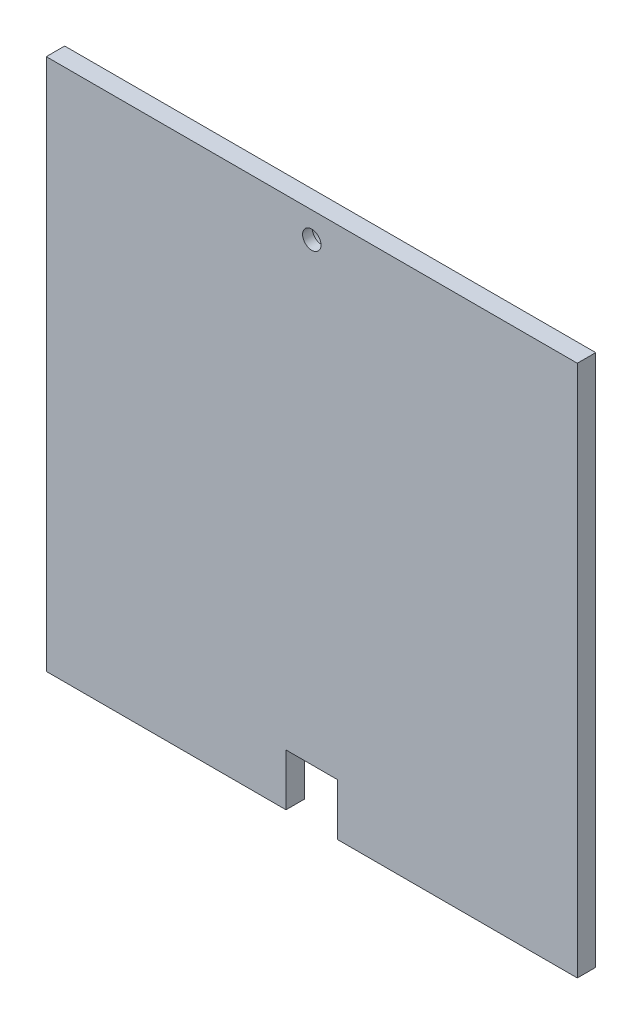
SolidWorks part; units mm, degrees
ref_plane "Plan de face" through (0, 0, 0) normal (0, 0, 1) x (1, 0, 0)
ref_plane "Plan de dessus" through (0, 0, 0) normal (0, 1, 0) x (1, 0, 0)
ref_plane "Plan de droite" through (0, 0, 0) normal (1, 0, 0) x (0, 0, -1)
sketch "Esquisse1" plane through (0, 0, 0) normal (0, 0, 1) x (1, 0, 0)
  line L0 (-83.3981, -1000) -> (-125.3981, -1000) construction
  line L1 (164.0336, 0) -> (-268.4317, 0)
  line L2 (164.0336, 0) -> (164.0336, -1000)
  line L3 (164.0336, -1000) -> (-268.4317, -1000)
  line L4 (-268.4317, 0) -> (-268.4317, -1000)
  line L5 (164.0336, 0) -> (-268.4317, -1000) construction
  line L6 (164.0336, -1000) -> (-268.4317, 0) construction
  line L7 (-83.3981, 0) -> (-125.3981, 0) construction
  point P0 (-52.199, -500)
extrude "Boss.-Extru.1" add sketch "Esquisse1" along normal blind 15
sketch "Esquisse2" plane through (164.0336, 0, 0) normal (1, 0, 0) x (0, 0, -1)
  line L0 (0, -1000) -> (0, 0) construction
  line L1 (-15, -1000) -> (0, -1000)
  line L2 (-15, -1000) -> (-15, -820)
  line L3 (-15, -820) -> (0, -820)
  line L4 (0, -1000) -> (0, -820)
  dimension "D1" = 180
extrude "Enlèv. mat.-Extru.1" cut sketch "Esquisse2" against normal through all
sketch "Esquisse3" plane through (-268.4317, 0, 0) normal (-1, 0, 0) x (0, 0, 1)
  line L0 (0, 0) -> (0, -820) construction
  line L1 (15, 0) -> (0, 0)
  line L2 (15, 0) -> (15, -386.4296)
  line L3 (15, -386.4296) -> (0, -386.4296)
  line L4 (0, 0) -> (0, -386.4296)
extrude "Enlèv. mat.-Extru.2" cut sketch "Esquisse3" against normal through all
sketch "Esquisse4" plane through (0, 0, 0) normal (0, 0, -1) x (-1, 0, 0)
  line L0 (31.199, -816) -> (31.199, -782) construction
  line L1 (73.199, -820.2276) -> (31.199, -820.2276)
  line L2 (73.199, -820.2276) -> (73.199, -777.7724)
  line L3 (73.199, -777.7724) -> (31.199, -777.7724)
  line L4 (31.199, -820.2276) -> (31.199, -777.7724)
  line L5 (73.199, -820.2276) -> (31.199, -777.7724) construction
  line L6 (73.199, -777.7724) -> (31.199, -820.2276) construction
  line L7 (37.2586, -777.7724) -> (67.2586, -777.7724) construction
  point P0 (52.199, -799)
extrude "Enlèv. mat.-Extru.3" cut sketch "Esquisse4" against normal through all
sketch "Esquisse5" plane through (0, 0, 0) normal (0, 0, -1) x (-1, 0, 0)
  arc A0 (52.199, -418.4296) -> (52.199, -396.4296) centre (52.199, -407.4296) ccw construction
  arc A1 (52.199, -396.4296) -> (52.199, -418.4296) centre (52.199, -407.4296) ccw construction
  arc A2 (52.199, -418.4296) -> (52.199, -396.4296) centre (52.199, -407.4296) ccw
  arc A3 (52.199, -396.4296) -> (52.199, -418.4296) centre (52.199, -407.4296) ccw
extrude "Enlèv. mat.-Extru.4" cut sketch "Esquisse5" against normal blind 7
sketch "Esquisse6" plane through (0, 0, 7) normal (0, 0, -1) x (-1, 0, 0)
  circle A0 centre (52.199, -407.4296) radius 7.5
  dimension "D1" = 15
extrude "Enlèv. mat.-Extru.5" cut sketch "Esquisse6" against normal through all
